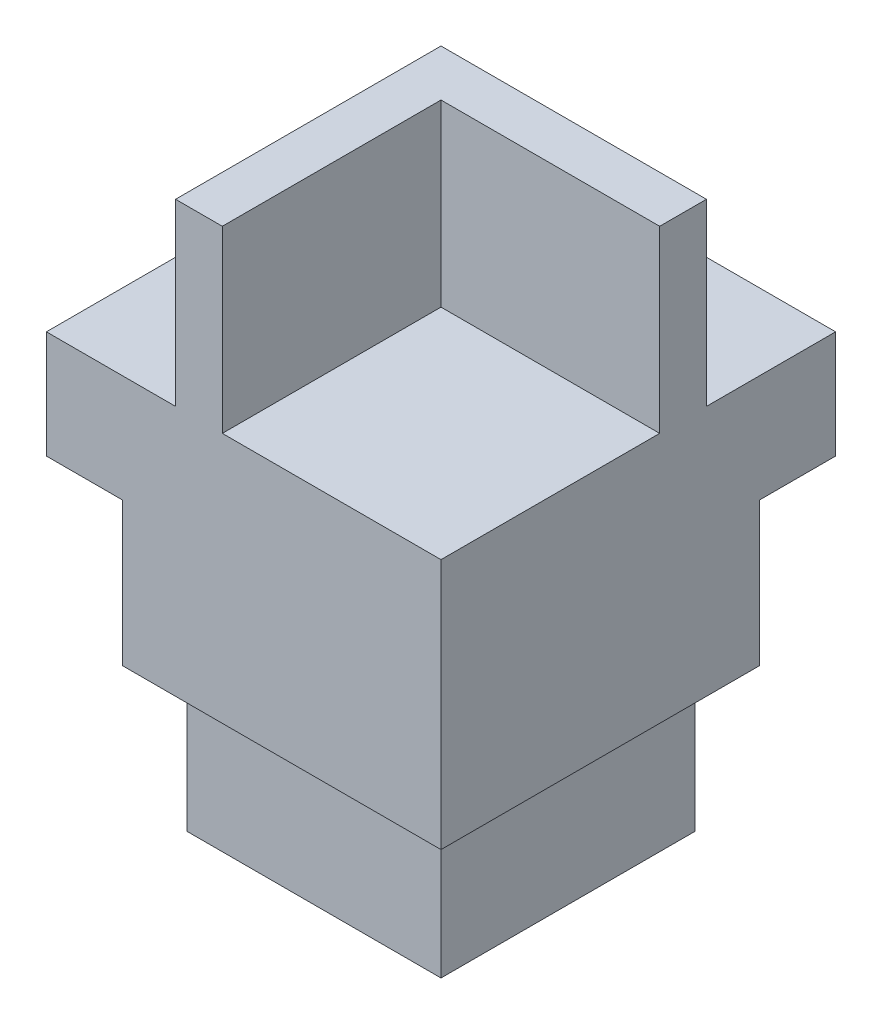
SolidWorks part; units mm, degrees
ref_plane "Front Plane" through (0, 0, 0) normal (0, 0, 1) x (1, 0, 0)
ref_plane "Top Plane" through (0, 0, 0) normal (0, 1, 0) x (1, 0, 0)
ref_plane "Right Plane" through (0, 0, 0) normal (1, 0, 0) x (0, 0, -1)
sketch "Sketch7" plane through (0, 0, 0) normal (0, 1, 0) x (1, 0, 0)
  line L1 (-15.54, -25.3407) -> (11.96, -25.3407)
  line L2 (-15.54, -25.3407) -> (-15.54, -52.8407)
  line L3 (-15.54, -52.8407) -> (11.96, -52.8407)
  line L4 (11.96, -25.3407) -> (11.96, -52.8407)
  dimension "D1" = 27.5
  dimension "D2" = 27.5
extrude "Boss-Extrude6" add sketch "Sketch7" along normal blind 40 separate body
sketch "Sketch8" plane through (0, 40, 0) normal (0, 1, 0) x (1, 0, 0)
  line L1 (11.96, -52.8407) -> (-3.28, -52.8407)
  line L2 (11.96, -52.8407) -> (11.96, -37.6007)
  line L3 (11.96, -37.6007) -> (-3.28, -37.6007)
  line L4 (-3.28, -52.8407) -> (-3.28, -37.6007)
  dimension "D1" = 15.24
  dimension "D2" = 15.24
extrude "Cut-Extrude2" cut sketch "Sketch8" against normal blind 12.5
sketch "Sketch9" plane through (0, 0, 0) normal (0, -1, 0) x (1, 0, 0)
  line L1 (11.96, 52.8407) -> (-10.24, 52.8407)
  line L2 (11.96, 52.8407) -> (11.96, 30.6407)
  line L3 (11.96, 30.6407) -> (-10.24, 30.6407)
  line L4 (-10.24, 52.8407) -> (-10.24, 30.6407)
  line L5 (11.96, 52.8407) -> (-15.54, 52.8407)
  line L6 (11.96, 52.8407) -> (11.96, 25.3407)
  line L7 (11.96, 25.3407) -> (-15.54, 25.3407)
  line L8 (-15.54, 52.8407) -> (-15.54, 25.3407)
  line M5 (-15.54, 52.8407) -> (-15.54, 25.3407)
  line M6 (-15.54, 25.3407) -> (11.96, 25.3407)
  line M7 (11.96, 25.3407) -> (11.96, 52.8407)
  line M8 (11.96, 52.8407) -> (-15.54, 52.8407)
  dimension "D1" = 22.2
  dimension "D2" = 22.2
extrude "Cut-Extrude3" cut sketch "Sketch9" against normal blind 20 contours L4 L3 M8 M5 M6 M7
sketch "Sketch10" plane through (0, 0, 0) normal (0, -1, 0) x (1, 0, 0)
  line L0 (-10.24, 41.7407) -> (11.96, 41.7407) construction
  line L2 (-10.24, 52.8407) -> (-10.24, 30.6407) construction
  line L3 (11.96, 52.8407) -> (11.96, 30.6407) construction
  line L5 (-7.99, 50.5907) -> (9.71, 50.5907)
  line L6 (-7.99, 50.5907) -> (-7.99, 32.8907)
  line L7 (-7.99, 32.8907) -> (9.71, 32.8907)
  line L8 (9.71, 50.5907) -> (9.71, 32.8907)
  line L9 (-7.99, 50.5907) -> (9.71, 32.8907) construction
  line L10 (-7.99, 32.8907) -> (9.71, 50.5907) construction
  line L11 (-10.24, 52.8407) -> (11.96, 52.8407)
  line L12 (-10.24, 52.8407) -> (-10.24, 30.6407)
  line L13 (-10.24, 30.6407) -> (11.96, 30.6407)
  line L14 (11.96, 52.8407) -> (11.96, 30.6407)
  line L15 (-10.24, 52.8407) -> (11.96, 30.6407) construction
  line L16 (-10.24, 30.6407) -> (11.96, 52.8407) construction
  point P6 (0.86, 41.7407)
  point P11 (0.86, 41.7407)
  dimension "D1" = 17.7
  dimension "D2" = 17.7
extrude "Cut-Extrude4" cut sketch "Sketch10" against normal blind 10
sketch "Sketch11" plane through (0, 40, 0) normal (0, 1, 0) x (1, 0, 0)
  line L1 (11.96, -25.3407) -> (-10.5577, -25.3407)
  line L2 (11.96, -25.3407) -> (11.96, -34.3407)
  line L3 (11.96, -34.3407) -> (-6.54, -34.3407)
  line L5 (-15.54, -52.8407) -> (-6.54, -52.8407)
  line L6 (-15.54, -52.8407) -> (-15.54, -25.3407)
  line L7 (-15.54, -25.3407) -> (-4.5646, -25.3407)
  line L8 (-6.54, -52.8407) -> (-6.54, -34.3407)
  line M6 (11.96, -37.6007) -> (11.96, -25.3407)
  line M7 (11.96, -25.3407) -> (-15.54, -25.3407)
  line M8 (-15.54, -25.3407) -> (-15.54, -52.8407)
  line M9 (-15.54, -52.8407) -> (-3.28, -52.8407)
  dimension "D1" = 9
  dimension "D2" = 9
extrude "Cut-Extrude5" cut sketch "Sketch11" against normal blind 12.5 contours L8 L3 L1 M9 M6 M7 M8
